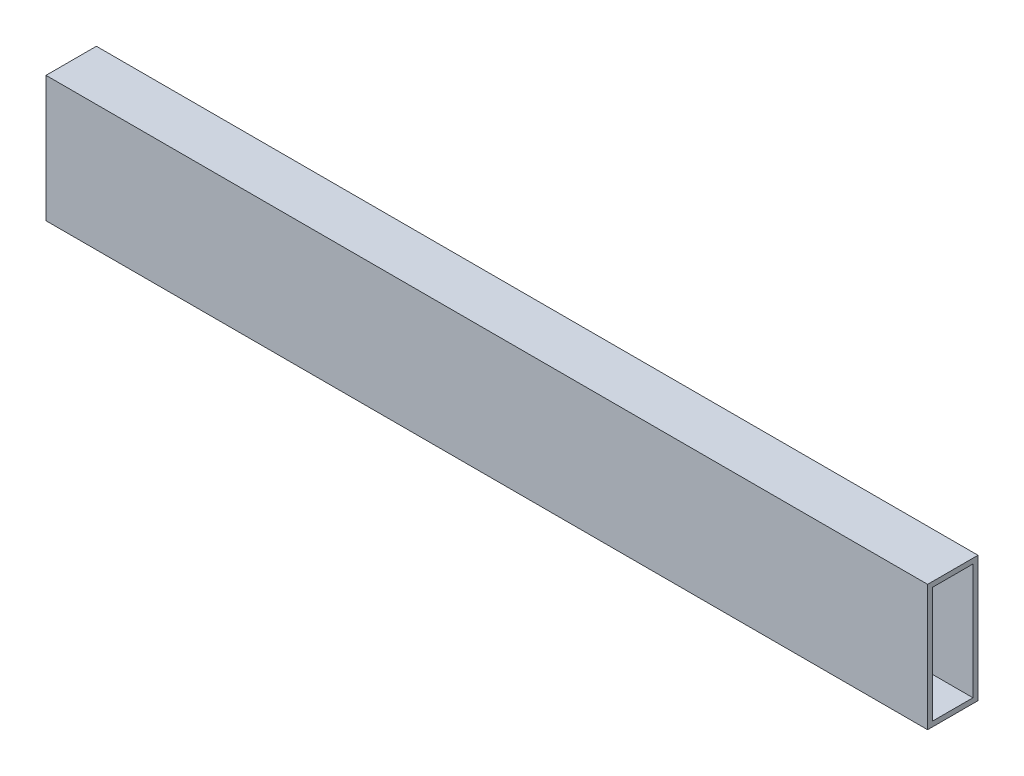
SolidWorks part; units mm, degrees
ref_plane "Спереди" through (0, 0, 0) normal (0, 0, 1) x (1, 0, 0)
ref_plane "Сверху" through (0, 0, 0) normal (0, 1, 0) x (1, 0, 0)
ref_plane "Справа" through (0, 0, 0) normal (1, 0, 0) x (0, 0, -1)
sketch "Эскиз1" plane through (0, 0, 0) normal (1, 0, 0) x (0, 0, -1)
  line L1 (-10, -25) -> (10, -25)
  line L2 (-10, -25) -> (-10, 25)
  line L3 (-10, 25) -> (10, 25)
  line L4 (10, -25) -> (10, 25)
  line L5 (-10, -25) -> (10, 25) construction
  line L6 (-10, 25) -> (10, -25) construction
  line L7 (-8, -23) -> (8, -23)
  line L8 (-8, -23) -> (-8, 23)
  line L9 (-8, 23) -> (8, 23)
  line L10 (8, -23) -> (8, 23)
  line L11 (-8, -23) -> (8, 23) construction
  line L12 (-8, 23) -> (8, -23) construction
  point P0 (0, 0)
  point P5 (0, 0)
  dimension "D1" = 50
  dimension "D2" = 20
  dimension "D3" = 2
  dimension "D4" = 2
extrude "Бобышка-Вытянуть1" add sketch "Эскиз1" along normal blind 350
